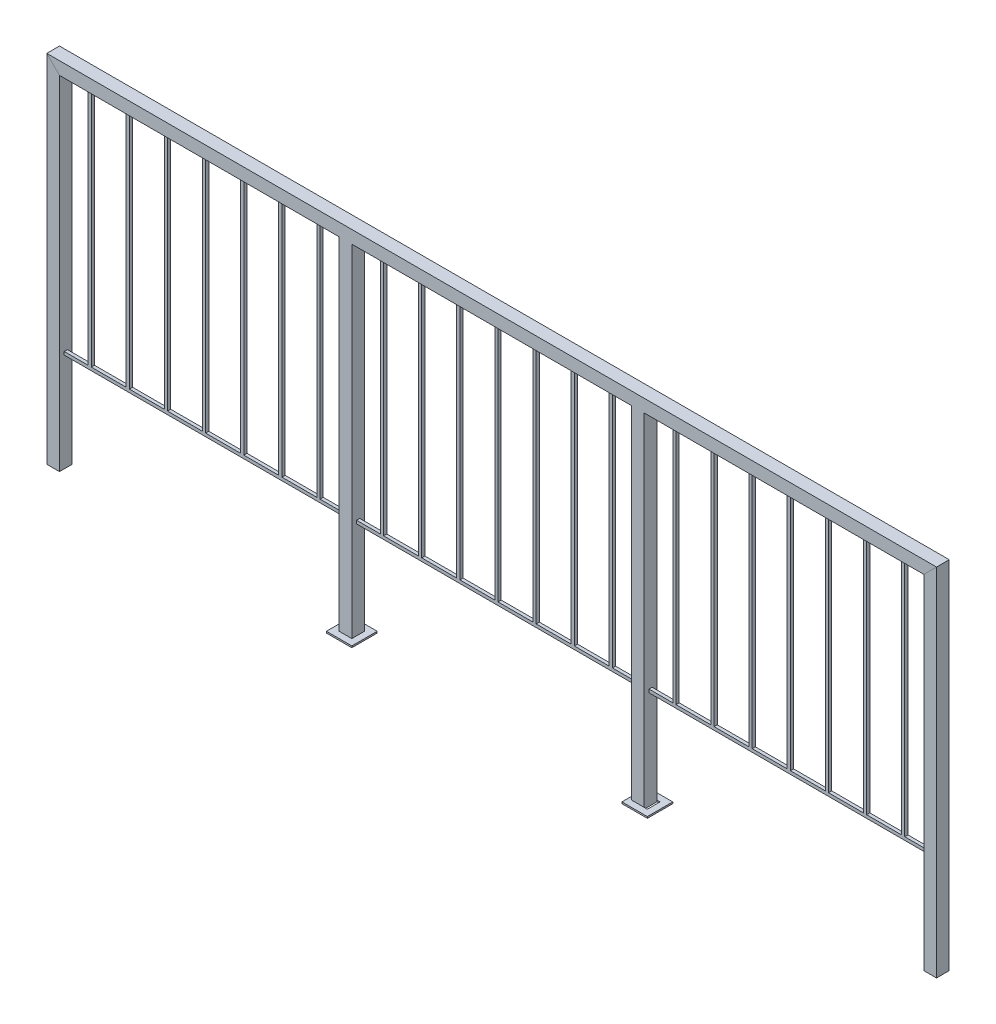
SolidWorks part; units mm, degrees
material "AISI 1020"
ref_plane "Спереди" through (0, 0, 0) normal (0, 0, 1) x (1, 0, 0)
ref_plane "Сверху" through (0, 0, 0) normal (0, 1, 0) x (1, 0, 0)
ref_plane "Справа" through (0, 0, 0) normal (1, 0, 0) x (0, 0, -1)
other "Configuration Table"
sketch3d "Трехмерный эскиз1"
  line L0 (0, 0, 0) -> (0, 1100, 0)
  line L1 (0, 1100, 0) -> (2760, 1100, 0)
  line L2 (2760, 1100, 0) -> (2760, 0, 0)
  line L3 (0, 0, 0) -> (2760, 0, 0) construction
  point P5 (933.3333, 143.1196, 0)
  point P6 (0, 0, 0)
  point P7 (0, 0, 0)
  point P9 (2840.2693, 1100, 0)
  dimension "D1" = 2760
  dimension "D2" = 1100
sketch "Эскиз2" plane through (0, 0, 0) normal (0, 1, 0) x (1, 0, 0)
  line L1 (-20, -20) -> (20, -20)
  line L2 (-20, -20) -> (-20, 20)
  line L3 (-20, 20) -> (20, 20)
  line L4 (20, -20) -> (20, 20)
  line L5 (-20, -20) -> (20, 20) construction
  line L6 (-20, 20) -> (20, -20) construction
  point P0 (0, 0)
  dimension "D1" = 40
sweep "По траектории2" add profiles "Эскиз2" path "Трехмерный эскиз1"
sketch "Эскиз4" plane through (0, 1080, 0) normal (0, -1, 0) x (1, 0, 0)
  line L6 (20, 20) -> (2740, 20) construction
  line L11 (900, -20) -> (940, -20)
  line L12 (900, -20) -> (900, 20)
  line L13 (900, 20) -> (940, 20)
  line L14 (940, -20) -> (940, 20)
  line L15 (900, -20) -> (940, 20) construction
  line L16 (900, 20) -> (940, -20) construction
  line L17 (0, 0) -> (920, 0) construction
  line L18 (1820, -20) -> (1860, -20)
  line L19 (1820, -20) -> (1820, 20)
  line L20 (1820, 20) -> (1860, 20)
  line L21 (1860, -20) -> (1860, 20)
  line L22 (1820, -20) -> (1860, 20) construction
  line L23 (1820, 20) -> (1860, -20) construction
  line L24 (920, 0) -> (1840, 0) construction
  line L25 (1840, 0) -> (2760, 0) construction
  line L26 (2760, 20) -> (2760, 0) construction
  line L27 (2780, 20) -> (2740, 20) construction
  line L28 (20, -20) -> (2740, -20) construction
  point P0 (920, 0)
  point P7 (1840, 0)
  point P16 (874.8019, -20)
  point P23 (1183.9537, -20)
extrude "Бобышка-Вытянуть1" add sketch "Эскиз4" along normal up to surface (1080 mm away) up to face at (0, 0, 0)
sketch "Эскиз5" plane through (20, 0, 0) normal (1, 0, 0) x (0, 0, -1)
  line L0 (-20, 315) -> (20, 315) construction
  line L1 (-5, 310) -> (5, 310)
  line L2 (-5, 310) -> (-5, 320)
  line L3 (-5, 320) -> (5, 320)
  line L4 (5, 310) -> (5, 320)
  line L5 (-5, 310) -> (5, 320) construction
  line L6 (-5, 320) -> (5, 310) construction
  line L7 (-20, 0) -> (-20, 1080) construction
  line L8 (20, 0) -> (20, 1080) construction
  line L9 (20, 1080) -> (-20, 1080) construction
  point P0 (0, 315)
  point P11 (0, 262.3567)
  dimension "D1" = 10
  dimension "D2" = 760
extrude "Бобышка-Вытянуть2" add sketch "Эскиз5" along normal up to surface (2720 mm away) up to face at (2740, 540, 0)
sketch "Эскиз6" plane through (0, 320, 0) normal (0, 1, 0) x (1, 0, 0)
  line L0 (1820, 5) -> (940, 5) construction
  line L1 (1375, -5) -> (1385, -5)
  line L2 (1375, -5) -> (1375, 5)
  line L3 (1375, 5) -> (1385, 5)
  line L4 (1385, -5) -> (1385, 5)
  line L5 (1375, -5) -> (1385, 5) construction
  line L6 (1375, 5) -> (1385, -5) construction
  line L7 (1820, -5) -> (940, -5) construction
  line L9 (940, 0) -> (1820, 0) construction
  line L10 (940, 5) -> (940, -5) construction
  line L11 (1820, -5) -> (1820, 5) construction
  point P0 (1380, 0)
  point P7 (1380, 0)
  point P16 (1400, 0)
extrude "Бобышка-Вытянуть3" add sketch "Эскиз6" along normal up to surface (760 mm away) up to face at (1380, 1080, 0)
pattern_linear "Линейный массив2" count 4 spacing 120 along (-1, 0, 0) count 4 spacing 120 along (1, 0, 0) of "Бобышка-Вытянуть3"
pattern_linear "Линейный массив3" count 2 spacing 920 along (-1, 0, 0) count 2 spacing 920 along (1, 0, 0) of "Бобышка-Вытянуть3", "Линейный массив2"
sketch "Эскиз7" plane through (0, 0, 0) normal (0, 1, 0) x (-1, 0, 0)
  line L1 (-960, -40) -> (-880, -40)
  line L2 (-960, -40) -> (-960, 40)
  line L3 (-960, 40) -> (-880, 40)
  line L4 (-880, -40) -> (-880, 40)
  line L5 (-960, -40) -> (-880, 40) construction
  line L6 (-960, 40) -> (-880, -40) construction
  line L7 (-900, -20) -> (-940, -20)
  line L8 (-900, -20) -> (-900, 20)
  line L9 (-900, 20) -> (-940, 20)
  line L10 (-940, -20) -> (-940, 20)
  line L11 (-900, -20) -> (-940, 20) construction
  line L12 (-900, 20) -> (-940, -20) construction
  point P0 (-920, 0)
  point P6 (-944.9496, 11.3815)
  point P7 (-953.3333, 20)
  point P8 (-920, 0)
  point P14 (-913.3333, -20)
  point P16 (-933.3333, 0)
  dimension "D1" = 80
extrude "Бобышка-Вытянуть4" add sketch "Эскиз7" along normal blind 5
pattern_linear "Линейный массив4" count 2 spacing 930 along (1, 0, 0) of "Бобышка-Вытянуть4"
